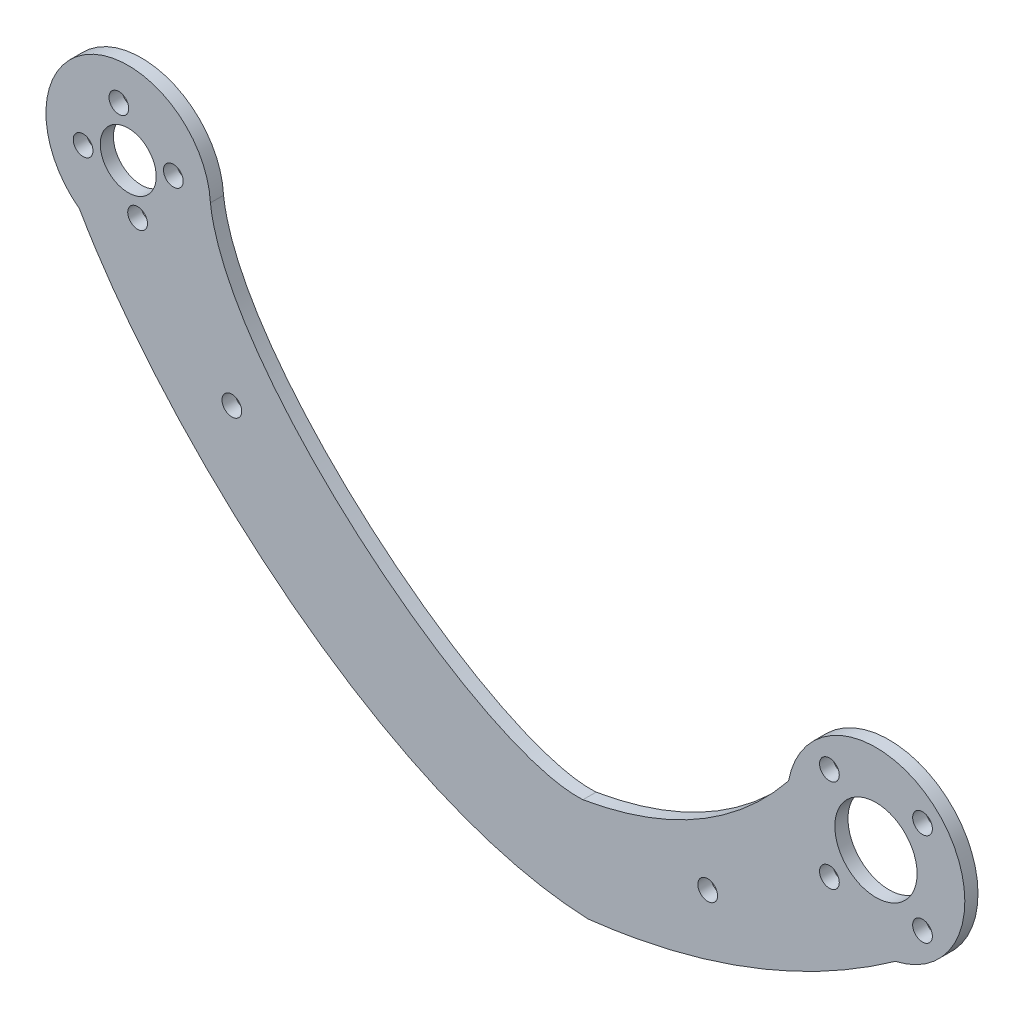
SolidWorks part; units mm, degrees
ref_plane "前视基准面" through (0, 0, 0) normal (0, 0, 1) x (1, 0, 0)
ref_plane "上视基准面" through (0, 0, 0) normal (0, 1, 0) x (1, 0, 0)
ref_plane "右视基准面" through (0, 0, 0) normal (1, 0, 0) x (0, 0, -1)
other "Configuration Table"
sketch "草图1" plane through (0, 0, 0) normal (0, 0, 1) x (1, 0, 0)
  circle A0 centre (0, 0) radius 13.5
  point P0 (0, 0)
  line B0 (-70.9851, 36.1523) -> (-113.5823, 33.9244)
  arc B1 (5.8927, -11.0239) -> (-11.6176, 4.6132) centre (0, 0) ccw
  arc B2 (-101.0993, 34.5773) -> (-120.9882, 23.8546) centre (-113.5823, 33.9244) ccw
  spline B3 degree 3 poles (-44.5149, -15.6481) (-60.4932, -16.621) (-98.7194, 13.994) (-101.0993, 34.5773) knots 0 0 0 0 1 1 1 1
  spline B4 degree 2 poles (5.8927, -11.0239) (-16.2083, -27.8197) (-43.715, -30.9419) knots 0 0 0 1 1 1
  spline B5 degree 3 poles (-43.715, -30.9419) (-74.6559, -29.7722) (-107.9347, 0.9093) (-120.9882, 23.8546) knots 0 0 0 0 1 1 1 1
  spline B6 degree 2 poles (-44.5149, -15.6481) (-23.755, -12.0499) (-11.6176, 4.6132) knots 0 0 0 1 1 1
  dimension "D1" = 27
sketch_block_instance "Block5-1"
sketch_block "Block5" parameters "D1"=25, "D14"=79.1954, "D15"=48.0238, "D17"=92.8889, "D18"=42.1388, "D19"=62.1612, "D2"=5.3089, "D3"=16.6697, "D4"=25.1002, "D5"=50.5803, "D6"=74.3089, "D7"=104.4643, "D8"=116.9643, "D9"=124.8861, "D10"=135.8089, "D11"=34.5967, "D12"=39.8104, "D13"=51.127, "D16"=68.4269
extrude "凸台-拉伸1" add sketch "草图1" along normal blind 2
sketch "草图2" plane through (0, 0, 0) normal (0, 0, 1) x (1, 0, 0)
  line L0 (0, 0) -> (0, 56.3072) construction
  line L1 (-7.0711, 7.0711) -> (0, 0) construction
  line L2 (-113.5823, 33.9244) -> (0, 0) construction
  line L3 (-56.7911, 16.9622) -> (-30.8992, 103.6508) construction
  line L4 (-103.7915, 35.9592) -> (-113.5823, 33.9244) construction
  line L5 (-115.6171, 43.7152) -> (-113.5823, 33.9244) construction
  line L6 (-103.7915, 35.9592) -> (-113.5823, 33.9244) construction
  line L7 (-111.5474, 24.1336) -> (-113.5823, 33.9244) construction
  line L8 (-123.3731, 31.8896) -> (-113.5823, 33.9244) construction
  circle A0 centre (0, 0) radius 6.25
  circle A1 centre (-7.0711, 7.0711) radius 1.5
  circle A2 centre (7.0711, 7.0711) radius 1.5
  circle A3 centre (7.0711, -7.0711) radius 1.5
  circle A4 centre (-7.0711, -7.0711) radius 1.5
  circle A5 centre (-113.5823, 33.9244) radius 4.25
  circle A6 centre (-106.7287, 35.3488) radius 1.5
  circle A7 centre (-112.1579, 27.0709) radius 1.5
  circle A8 centre (-120.4358, 32.5001) radius 1.5
  circle A10 centre (-115.0066, 40.778) radius 1.5
  point P8 (-56.7911, 16.9622)
  point P15 (0, 0)
  point P35 (-113.5823, 33.9244)
  dimension "D1" = 12.5
  dimension "D2" = 3
  dimension "D6" = 8.5
  dimension "D7" = 3
  dimension "D8" = 7
  dimension "D3" = 45
  dimension "D4" = 10
  dimension "D5" = 4
  dimension "D9" = 4
extrude "切除-拉伸2" cut sketch "草图2" along normal through all
sketch "草图3" plane through (0, 0, 0) normal (0, 0, 1) x (1, 0, 0)
  line L0 (-113.5823, 33.9244) -> (-69.4661, -34.4033) construction
  line L1 (0, 0) -> (-63.0101, -44.4968) construction
  circle A0 centre (-97.8402, 9.543) radius 1.5
  circle A1 centre (-25.5617, -18.0513) radius 1.5
  dimension "D1" = 3
extrude "切除-拉伸3" cut sketch "草图3" along normal through all
sketch "草图4" plane through (0, 0, 2) normal (0, 0, 1) x (1, 0, 0)
  point P0 (-113.5823, 33.9244)
  point P1 (0, 0)
